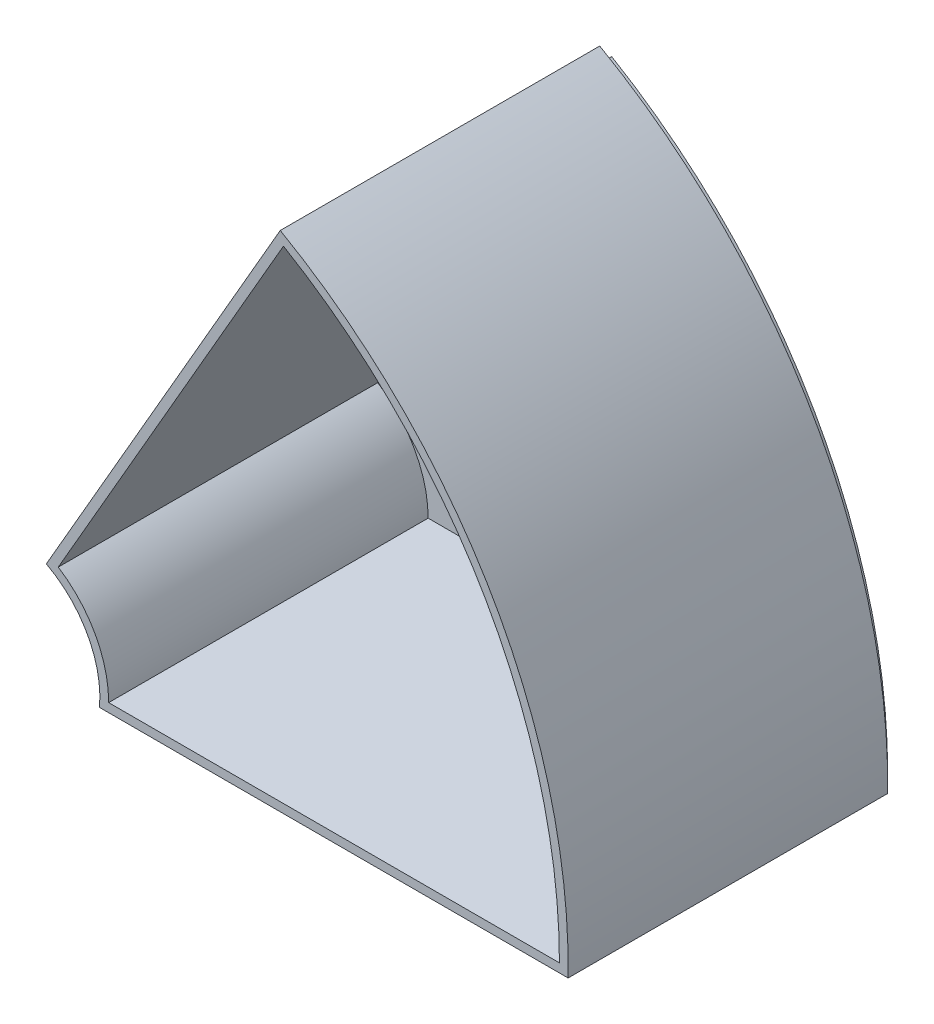
SolidWorks part; units mm, degrees
ref_plane "前视基准面" through (0, 0, 0) normal (0, 0, 1) x (1, 0, 0)
ref_plane "上视基准面" through (0, 0, 0) normal (0, 1, 0) x (1, 0, 0)
ref_plane "右视基准面" through (0, 0, 0) normal (1, 0, 0) x (0, 0, -1)
other "Configuration Table"
sketch "草图1" plane through (0, 0, 0) normal (0, 0, 1) x (1, 0, 0)
  line L0 (25, 0) -> (128, 0)
  line L1 (13.4819, 21.0532) -> (64.9412, 110.3025)
  arc A0 (128, 0) -> (64.9412, 110.3025) centre (0, 0) ccw
  arc A1 (13.4819, 21.0532) -> (25, 0) centre (0, 0) cw
  dimension "D1" = 25
  dimension "D2" = 128
extrude "凸台-拉伸1" add sketch "草图1" along normal blind 2
sketch "草图2" plane through (0, 0, 2) normal (0, 0, 1) x (1, 0, 0)
  line L2 (64.9412, 110.3025) -> (13.4819, 21.0532)
  line L3 (25, 0) -> (128, 0)
  line L4 (64.9412, 110.3025) -> (13.4819, 21.0532)
  line L5 (25, 0) -> (128, 0)
  arc A1 (128, 0) -> (64.9412, 110.3025) centre (0, 0) ccw
  arc A2 (128, 0) -> (64.9412, 110.3025) centre (0, 0) ccw
  arc A4 (25, 0) -> (13.4819, 21.0532) centre (0, 0) ccw
  arc A5 (25, 0) -> (13.4819, 21.0532) centre (0, 0) ccw
  dimension "D1" = 0
extrude "拉伸-薄壁1" add sketch "草图2" along normal blind 73 separate body thin
